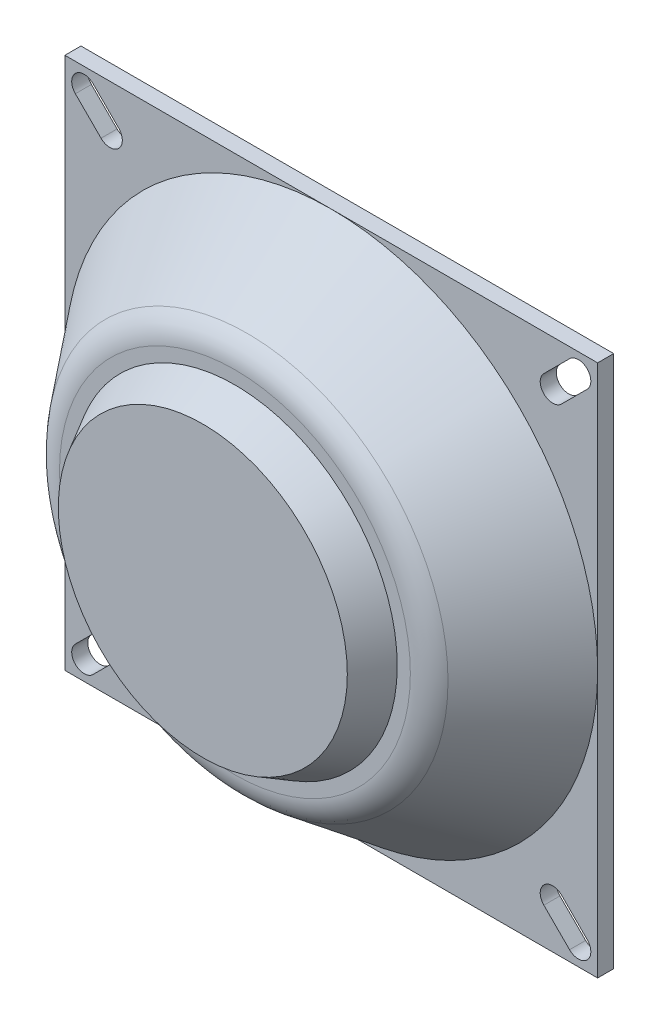
SolidWorks part; units mm, degrees
ref_plane "Front Plane" through (0, 0, 0) normal (0, 0, 1) x (1, 0, 0)
ref_plane "Top Plane" through (0, 0, 0) normal (0, 1, 0) x (1, 0, 0)
ref_plane "Right Plane" through (0, 0, 0) normal (1, 0, 0) x (0, 0, -1)
sketch "Sketch4" plane through (0, 0, 0) normal (0, 0, 1) x (1, 0, 0)
  line L5 (-365.3598, 176.7949) -> (-245.3598, 176.7949)
  line L6 (-365.3598, 176.7949) -> (-365.3598, 56.7949)
  line L9 (-365.3598, 56.7949) -> (-245.3598, 56.7949)
  line L10 (-245.3598, 176.7949) -> (-245.3598, 56.7949)
  line L11 (-365.3598, 176.7949) -> (-245.3598, 56.7949) construction
  line L12 (-365.3598, 56.7949) -> (-245.3598, 176.7949) construction
  arc A0 (-299.6687, 180.8326) -> (-300.0877, 180.9274) centre (-313.2536, 121.7932) ccw
  circle A4 centre (-305.3598, 116.7949) radius 60
  circle A5 centre (-305.3598, 116.7949) radius 45
  point P9 (-305.3598, 116.7949)
  point P13 (-418.3831, 208.3523)
  point P14 (-393.0656, 164.7961)
  point P15 (-337.7537, 167.8517)
  dimension "D3" = 90
  dimension "D1" = 120
  dimension "D2" = 120
ref_plane "Plane1" through (0, 0, -10) normal (0, 0, 1) x (1, 0, 0)
extrude "Boss-Extrude1" add sketch "Sketch4" against normal up to surface (10 mm away) draft 29 contours A5
ref_plane "Plane2" through (0, 0, -40) normal (0, 0, 1) x (1, 0, 0)
sketch "Sketch7" plane through (0, 0, -10) normal (0, 0, 1) x (1, 0, 0)
  circle A0 centre (-305.3598, 116.7949) radius 59.5087
sketch "Sketch8" plane through (0, 0, -40) normal (0, 0, 1) x (1, 0, 0)
  circle A0 centre (-305.3598, 116.7949) radius 75
  dimension "D1" = 150
extrude "Boss-Extrude2" add sketch "Sketch7" against normal up to surface (30 mm away) draft 38
fillet "Fillet1" radius 10 1 edges at (-245.8511, 116.7949, -10)
sketch "Sketch9" plane through (0, 0, -40) normal (0, 0, 1) x (1, 0, 0)
  line L0 (-228.4125, 193.7421) -> (-236.4125, 185.7421) construction
  line L1 (-222.4125, 199.7421) -> (-388.307, 199.7421)
  line L2 (-222.4125, 199.7421) -> (-222.4125, 33.8476)
  line L3 (-222.4125, 33.8476) -> (-388.307, 33.8476)
  line L4 (-388.307, 199.7421) -> (-388.307, 33.8476)
  line L5 (-222.4125, 199.7421) -> (-388.307, 33.8476) construction
  line L6 (-222.4125, 33.8476) -> (-388.307, 199.7421) construction
  line L7 (-225.6708, 191.0004) -> (-233.6708, 183.0004)
  line L8 (-231.1542, 196.4838) -> (-239.1542, 188.4838)
  line L9 (-305.3598, 116.7949) -> (-305.3598, 199.7421) construction
  line L10 (-305.3598, 116.7949) -> (-222.4125, 116.7949) construction
  line L11 (-382.307, 193.7421) -> (-374.307, 185.7421) construction
  line L12 (-385.0487, 191.0004) -> (-377.0487, 183.0004)
  line L13 (-379.5653, 196.4838) -> (-371.5653, 188.4838)
  line L14 (-382.307, 39.8476) -> (-374.307, 47.8476) construction
  line L15 (-385.0487, 42.5893) -> (-377.0487, 50.5893)
  line L16 (-379.5653, 37.1059) -> (-371.5653, 45.1059)
  line L17 (-228.4125, 39.8476) -> (-236.4125, 47.8476) construction
  line L18 (-225.6708, 42.5893) -> (-233.6708, 50.5893)
  line L19 (-231.1542, 37.1059) -> (-239.1542, 45.1059)
  circle A0 centre (-305.3598, 116.7949) radius 82.9472 construction
  arc A1 (-225.6708, 191.0004) -> (-231.1542, 196.4838) centre (-228.4125, 193.7421) ccw
  arc A2 (-239.1542, 188.4838) -> (-233.6708, 183.0004) centre (-236.4125, 185.7421) ccw
  arc A3 (-385.0487, 191.0004) -> (-379.5653, 196.4838) centre (-382.307, 193.7421) cw
  arc A4 (-371.5653, 188.4838) -> (-377.0487, 183.0004) centre (-374.307, 185.7421) cw
  arc A5 (-385.0487, 42.5893) -> (-379.5653, 37.1059) centre (-382.307, 39.8476) ccw
  arc A6 (-371.5653, 45.1059) -> (-377.0487, 50.5893) centre (-374.307, 47.8476) ccw
  arc A7 (-225.6708, 42.5893) -> (-231.1542, 37.1059) centre (-228.4125, 39.8476) cw
  arc A8 (-239.1542, 45.1059) -> (-233.6708, 50.5893) centre (-236.4125, 47.8476) cw
  point P0 (-305.3598, 116.7949)
  point P7 (-305.3598, 199.7421)
  point P10 (-232.4125, 189.7421)
  point P20 (-378.307, 189.7421)
  point P27 (-378.307, 43.8476)
  point P34 (-232.4125, 43.8476)
  dimension "D3" = 3.8774
  dimension "D1" = 8
  dimension "D2" = 6
extrude "Boss-Extrude3" add sketch "Sketch9" against normal blind 5
